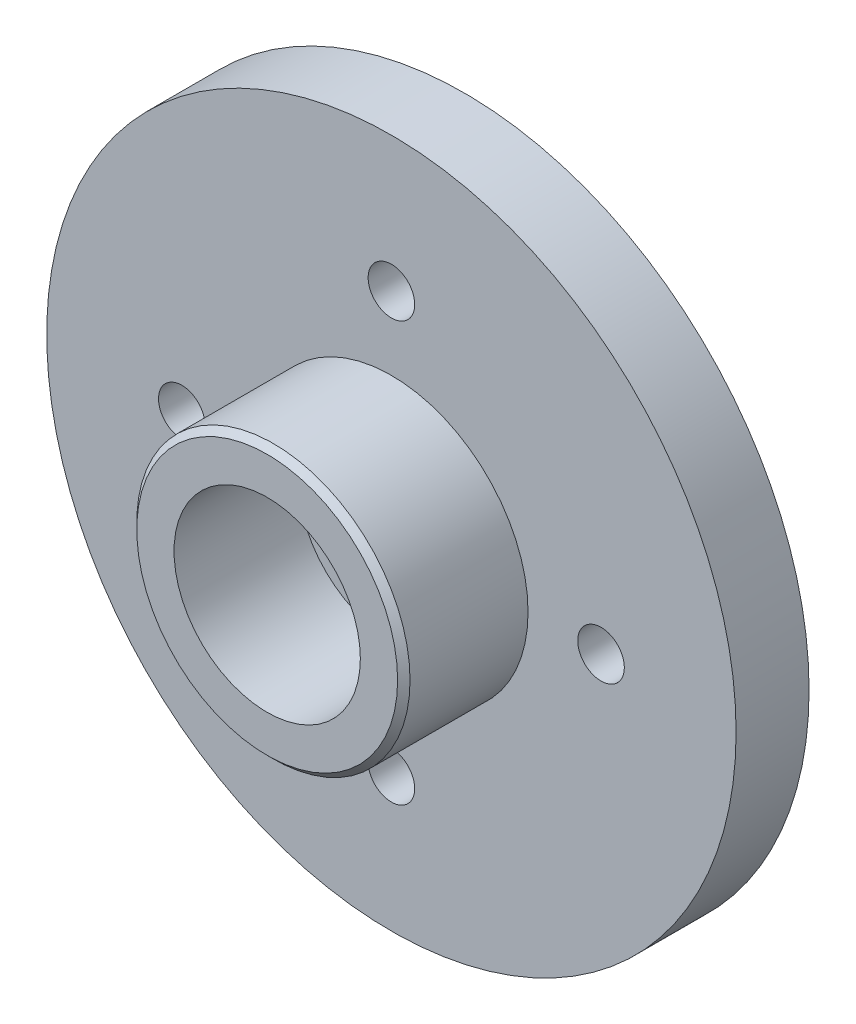
SolidWorks part; units mm, degrees
ref_plane "Plan de face" through (0, 0, 0) normal (0, 0, 1) x (1, 0, 0)
ref_plane "Plan de dessus" through (0, 0, 0) normal (0, 1, 0) x (1, 0, 0)
ref_plane "Plan de droite" through (0, 0, 0) normal (1, 0, 0) x (0, 0, -1)
sketch "Esquisse1" plane through (0, 0, 0) normal (0, 0, 1) x (1, 0, 0)
  line L0 (-14.3269, 0) -> (23.3202, 0) construction
  circle A0 centre (0, 0) radius 11.1
  circle A1 centre (0, 6.75) radius 1.5
  circle A2 centre (0, -6.75) radius 1.5
  dimension "D1" = 22.2
  dimension "D2" = 6.75
  dimension "D3" = 6.75
extrude "Boss.-Extru.1" add sketch "Esquisse1" along normal blind 2.35
sketch "Esquisse2" plane through (0, 0, 2.35) normal (0, 0, 1) x (1, 0, 0)
  line L0 (-19.6535, 0) -> (16.5225, 0) construction
  circle A0 centre (0, 0) radius 4.4
  circle A1 centre (0, 0) radius 3
  dimension "D1" = 8.8
extrude "Boss.-Extru.2" add sketch "Esquisse2" along normal blind 4
sketch "Esquisse3" plane through (0, 0, 2.35) normal (0, 0, 1) x (1, 0, 0)
  circle A0 centre (0, 0) radius 1.43
extrude "Enlèv. mat.-Extru.1" cut sketch "Esquisse3" against normal blind 4
chamfer "Chanfrein2" distance 0.2 angle 45 1 edges at (4.4, 0, 6.35)
sketch "Esquisse4" plane through (0, 0, 0) normal (0, 0, -1) x (-1, 0, 0)
  line L0 (-16.5845, 0) -> (16.3365, 0) construction
  circle A0 centre (-6.75, 0) radius 1.5
  circle A1 centre (6.75, 0) radius 1.5
  point P3 (0, 6.75)
  dimension "D1" = 6.75
  dimension "D2" = 6.75
extrude "Enlèv. mat.-Extru.2" cut sketch "Esquisse4" against normal blind 4
sketch "Esquisse5" plane through (0, 0, 2.35) normal (0, 0, 1) x (1, 0, 0)
  circle A0 centre (-6.75, 0) radius 0.75
  circle A1 centre (0, -6.75) radius 0.75
  circle A2 centre (0, 6.75) radius 0.75
  circle A3 centre (6.75, 0) radius 0.75
  circle A4 centre (-6.75, 0) radius 1.5
  circle A5 centre (0, -6.75) radius 1.5
  circle A6 centre (6.75, 0) radius 1.5
  circle A7 centre (0, 6.75) radius 1.5
extrude "Boss.-Extru.3" add sketch "Esquisse5" against normal blind 2.35
